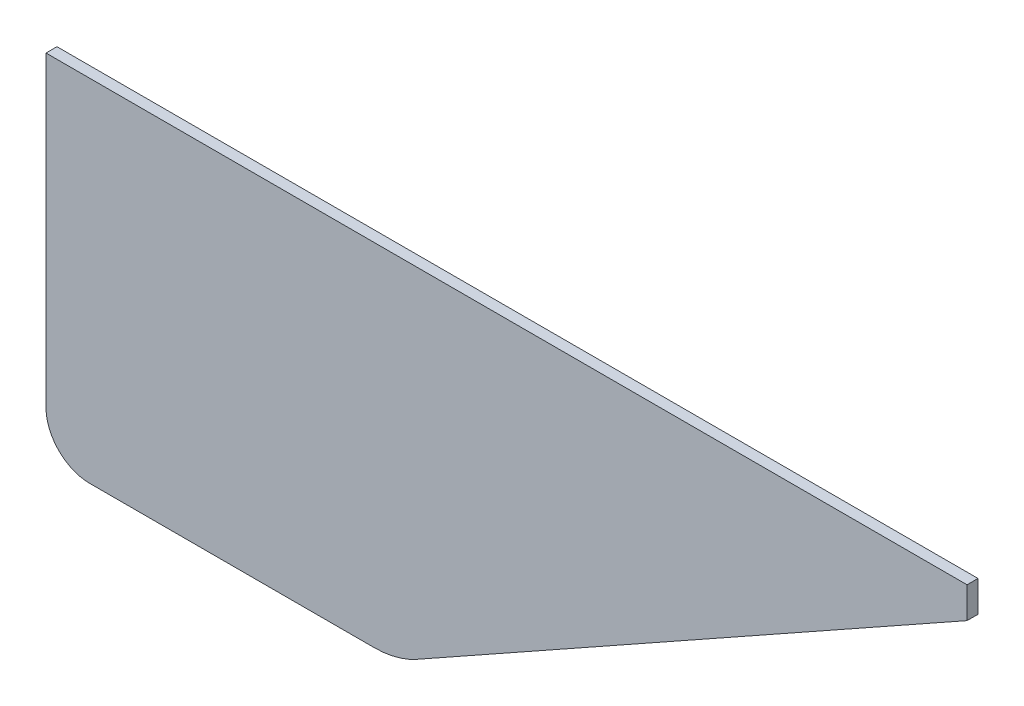
SolidWorks part; units mm, degrees
ref_plane "Front Plane" through (0, 0, 0) normal (0, 0, 1) x (1, 0, 0)
ref_plane "Top Plane" through (0, 0, 0) normal (0, 1, 0) x (1, 0, 0)
ref_plane "Right Plane" through (0, 0, 0) normal (1, 0, 0) x (0, 0, -1)
sketch "Sketch1" plane through (0, 0, 0) normal (0, 0, 1) x (1, 0, 0)
  line L0 (0, 0) -> (-133.35, 0)
  line L1 (-133.35, 0) -> (-133.35, -50.8)
  line L2 (-133.35, -50.8) -> (-82.55, -50.8)
  line L3 (-82.55, -50.8) -> (0, -4.5)
  line L4 (0, -4.5) -> (0, 0)
  dimension "D1" = 133.35
  dimension "D2" = 4.5
  dimension "D3" = 50.8
  dimension "D4" = 50.8
extrude "Boss-Extrude1" add sketch "Sketch1" along normal mid plane 1.5875
fillet "Fillet1" radius 6.35 1 edges at (-133.35, -50.8, 0)
fillet "Fillet2" radius 12.7 1 edges at (-82.55, -50.8, 0)
